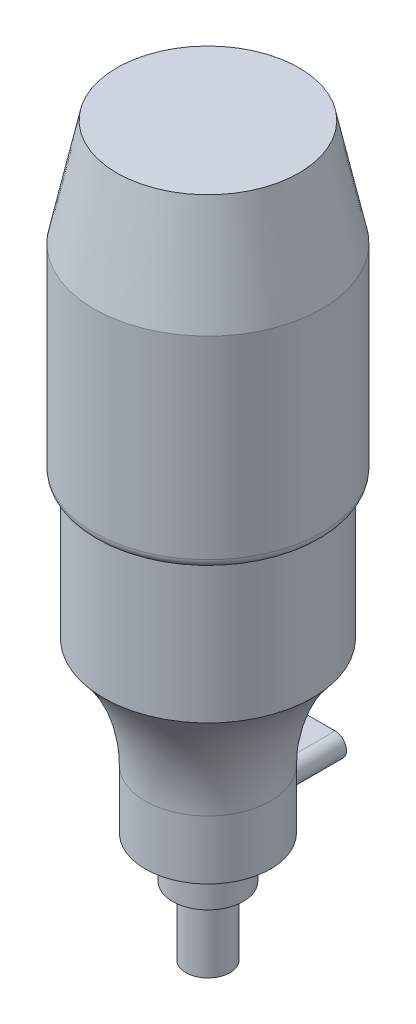
SolidWorks part; units mm, degrees
ref_plane "Plan de face" through (0, 0, 0) normal (0, 0, 1) x (1, 0, 0)
ref_plane "Plan de dessus" through (0, 0, 0) normal (0, 1, 0) x (1, 0, 0)
ref_plane "Plan de droite" through (0, 0, 0) normal (1, 0, 0) x (0, 0, -1)
ref_axis "Axe1" through (0, 182.175, 0) along (0, -1, 0)
sketch "Esquisse1" plane through (0, 0, 0) normal (0, 0, 1) x (1, 0, 0)
  line L0 (5.8, 0) -> (9.3, 0)
  line L1 (9.3, 0) -> (9.3, 11)
  line L2 (9.3, 11) -> (16.5, 11)
  line L3 (27.5, 55.5) -> (27.5, 92)
  line L4 (30, 94.5) -> (30, 145.5)
  line L5 (30, 145.5) -> (24, 173.5)
  line L6 (24, 173.5) -> (0, 173.5)
  line L7 (16.5, 11) -> (16.5, 26.5)
  line L8 (0, 0) -> (0, -18)
  line L9 (0, 182.175) -> (0, -8.675) construction
  line L10 (0, -18) -> (5.8, -18)
  line L11 (5.8, -18) -> (5.8, 0)
  line L12 (0, 0) -> (5.8, 0) construction
  arc A0 (16.5, 26.5) -> (27.5, 55.5) centre (60.2273, 26.5) cw
  arc A1 (27.5, 92) -> (30, 94.5) centre (27.5, 94.5) ccw
  dimension "D4" = 27.5
  dimension "D5" = 29
  dimension "D9" = 2.5
  dimension "D1" = 9.3
  dimension "D2" = 11
  dimension "D3" = 7.2
  dimension "D6" = 51
  dimension "D7" = 24
  dimension "D8" = 81.5
  dimension "D10" = 81
  dimension "D11" = 15.5
  dimension "D12" = 5.8
  dimension "D13" = 18
revolve "Révol.-Mince1" add sketch "Esquisse1" angle 360 about axis through (0, 182.175, 0) along (0, -1, 0) wall 1
ref_plane "Plan1" through (0, 0, -30) normal (0, 0, -1) x (-1, 0, 0)
sketch "Esquisse3" plane through (0, 0, -30) normal (0, 0, -1) x (-1, 0, 0)
  line L0 (24, 173.5) -> (-24, 173.5) construction
  line L1 (-19, 135.5) -> (19, 135.5)
  line L2 (-19, 135.5) -> (-19, 118)
  line L3 (-19, 118) -> (19, 118)
  line L4 (19, 135.5) -> (19, 118)
  point P4 (0, 118)
  dimension "D1" = 17.5
  dimension "D2" = 38
  dimension "D3" = 38
extrude "Enlèv. mat.-Extru.1" cut sketch "Esquisse3" against normal blind 10
sketch "Esquisse4" plane through (0, 0, -30) normal (0, 0, -1) x (-1, 0, 0)
  line L0 (-3.5, 21) -> (3.5, 21)
  line L1 (3.5, 15) -> (-3.5, 15)
  line L2 (-5.8, -18) -> (5.8, -18) construction
  arc A0 (3.5, 21) -> (3.5, 15) centre (3.5, 18) cw
  arc A1 (-3.5, 15) -> (-3.5, 21) centre (-3.5, 18) cw
  point P6 (0, 15)
  dimension "D2" = 13
  dimension "D1" = 6
  dimension "D3" = 39
extrude "Boss.-Extru.1" add sketch "Esquisse4" against normal up to next
